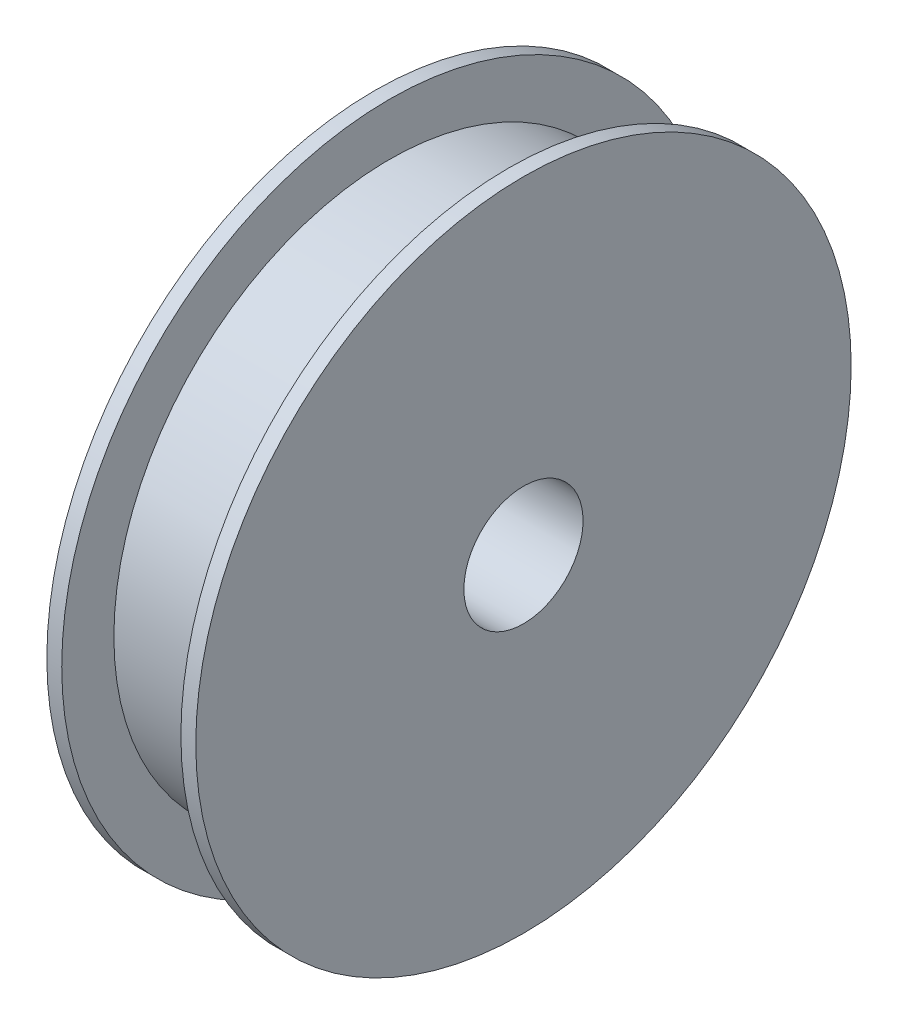
SolidWorks part; units mm, degrees
ref_plane "Front Plane" through (0, 0, 0) normal (0, 0, 1) x (1, 0, 0)
ref_plane "Top Plane" through (0, 0, 0) normal (0, 1, 0) x (1, 0, 0)
ref_plane "Right Plane" through (0, 0, 0) normal (1, 0, 0) x (0, 0, -1)
sketch "Sketch1" plane through (0, 0, 0) normal (0, 0, 1) x (1, 0, 0)
  line L0 (-58.1666, 0) -> (60.2282, 0) construction
  line L4 (59.2282, 22) -> (58.2282, 22)
  line L5 (58.2282, 22) -> (58.2282, 18.5)
  line L6 (58.2282, 18.5) -> (50.2282, 18.5)
  line L7 (50.2282, 18.5) -> (50.2282, 22)
  line L8 (50.2282, 22) -> (49.2282, 22)
  line L9 (49.2282, 22) -> (49.2282, 15)
  line L13 (42.2282, 10) -> (42.2282, 4)
  line L14 (42.2282, 4) -> (59.2282, 4)
  line L16 (49.2282, 10) -> (49.2282, 15)
  line L17 (59.2282, 22) -> (59.2282, 4)
  line L18 (42.2282, 10) -> (49.2282, 10)
  dimension "D1" = 7
  dimension "D2" = 10
  dimension "D3" = 4
  dimension "D4" = 10
  dimension "D5" = 1
  dimension "D6" = 18.5
  dimension "D7" = 22
  dimension "D8" = 1
revolve "Revolve1" add sketch "Sketch1" angle 360 about L0
